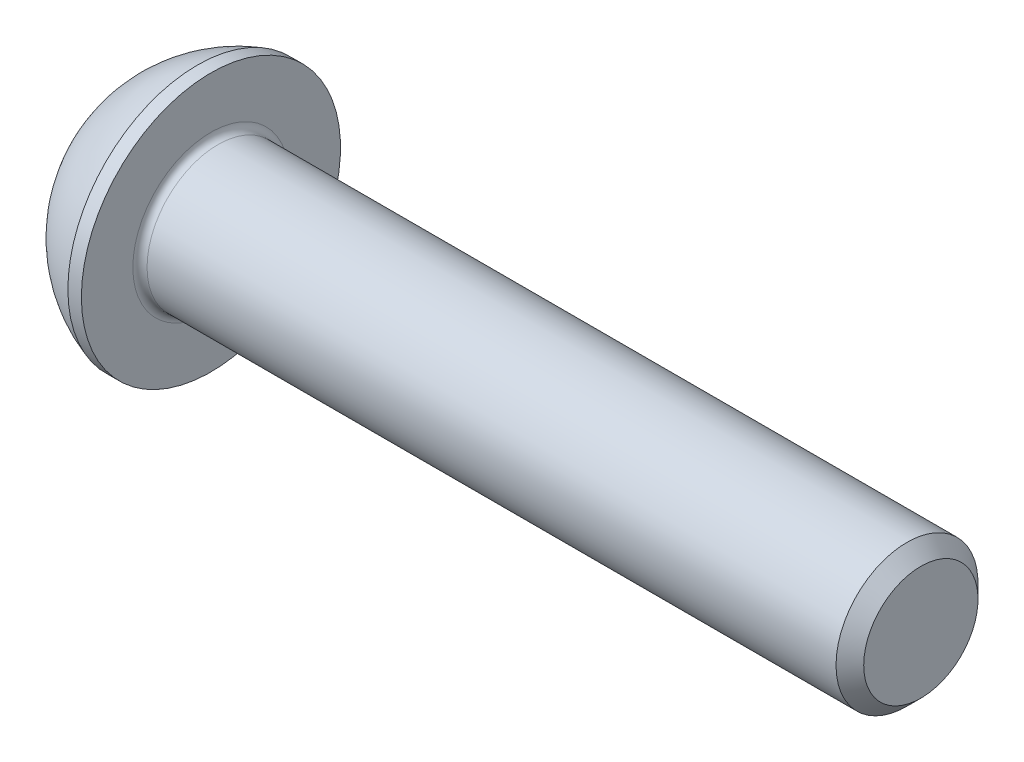
SolidWorks part; units mm, degrees
ref_plane "Plane1" through (0, 0, 0) normal (0, 0, 1) x (1, 0, 0)
ref_plane "Plane2" through (0, 0, 0) normal (0, 1, 0) x (1, 0, 0)
ref_plane "Plane3" through (0, 0, 0) normal (1, 0, 0) x (0, 0, -1)
sketch "BodySke" plane through (0, 0, 0) normal (0, 0, 1) x (1, 0, 0)
  line L0 (22.6, 0) -> (22.6, 1.61)
  line L1 (22.21, 2) -> (2.6, 2)
  line L2 (2.6, 2) -> (2.6, 3.65)
  line L3 (2.6, 3.65) -> (2.22, 3.65)
  line L4 (0, 0) -> (101.6, 0) construction
  line L5 (2.6, -3.65) -> (2.22, -3.65) construction
  line L6 (55.6768, -2) -> (2.6, -2) construction
  line L7 (22.6, 0) -> (0, 0)
  line L8 (0, 1.825) -> (0, -1.825) construction
  line L9 (0, 0) -> (0, 1.825)
  line L10 (22.6, 1.61) -> (22.21, 2)
  line L11 (22.6, -1.61) -> (22.21, -2) construction
  line L12 (3.3, 9.525) -> (3.3, -2) construction
  line L13 (2.6, 9.525) -> (2.6, -2) construction
  arc A1 (0, 1.825) -> (2.22, 3.65) centre (3.3604, 0) cw
  dimension "D1" = 3.65
  dimension "Diameter" = 4
  dimension "Length" = 20
  dimension "Head_dia" = 7.3
  dimension "Head_ht" = 2.6
  dimension "Head_side_ht" = 0.38
  dimension "Minor_dia" = 3.22
  dimension "Body_ch_ang" = 45
  dimension "Advance" = 0.7
  dimension "Thread_nom" = 20
revolve "BaseBody" add sketch "BodySke" angle 360 about L4
cosmetic thread "ThreadCosmetic" parameters "Thread_length"=18.6, "Thread_minor"=3.22
fillet "Fillet1" radius 0.2 1 edges at (2.6, 0, 2)
sketch "Sketch2" plane through (0, 0, 0) normal (0, 0, 1) x (1, 0, 0)
  line L0 (0, 1.25) -> (1.3, 1.25)
  line L1 (1.3, 1.25) -> (2.0217, 0)
  line L3 (2.0217, 0) -> (0, 0)
  line L4 (0, 0) -> (0, 1.25)
  line L5 (0, -1.25) -> (1.3, -1.25) construction
  line L6 (0, 0) -> (47.625, 0) construction
  dimension "D2" = 60
  dimension "PreBroach_depth" = 1.3
  dimension "PreBroach_dia" = 2.5
revolve "PreBroach" cut sketch "Sketch2" angle 360 about L6
sketch "Sketch3" plane through (0, 0, 0) normal (1, 0, 0) x (0, 0, -1)
  line L0 (-1.25, -0.7217) -> (-1.25, 0.7217)
  line L1 (-1.25, 0.7217) -> (0, 1.4434)
  line L2 (0, 1.4434) -> (1.25, 0.7217)
  line L3 (1.25, 0.7217) -> (1.25, -0.7217)
  line L4 (1.25, -0.7217) -> (0, -1.4434)
  line L5 (0, -1.4434) -> (-1.25, -0.7217)
  dimension "D1" = 1.25
  dimension "D2" = 1.25
  dimension "D3" = 2.5
  dimension "Hex_size" = 2.5
extrude "Hex" cut sketch "Sketch3" along normal blind 1.3
sketch "ThdSchSke" plane through (0, 0, 0) normal (0, 0, 1) x (1, 0, 0)
  line L0 (4, -1.61) -> (3.7269, -2)
  line L1 (4, -1.61) -> (4.2731, -2)
  line L2 (4.2731, -2) -> (4.2731, -2.5)
  line L3 (-3.175, 0) -> (5.1513, 0) construction
  line L5 (4.2731, -2.5) -> (3.7269, -2.5)
  line L6 (3.7269, -2.5) -> (3.7269, -2)
  dimension "Thread_minor" = 3.22
  dimension "Diameter" = 4
  dimension "Start" = 4
  dimension "SideAngle" = 55
  dimension "VeeAngle" = 70
  dimension "Overcut" = 5
revolve "ThreadSchematic" [suppressed] cut sketch "ThdSchSke" angle 360 about L3
pattern_linear "ThdSchPat" [suppressed]
equation "\"D1@BodySke\" = \"Head_dia@BodySke\" * .5"
equation "\"Thread_minor@ThreadCosmetic\" = \"Minor_dia@BodySke\""
equation "\"D1@Sketch3\" = \"Hex_size@Sketch3\" / 2"
equation "\"D2@Sketch3\" = \"D1@Sketch3\""
equation "\"D3@Sketch3\" = \"Hex_size@Sketch3\""
equation "\"Thread_length@ThreadCosmetic\" = ((sgn( (\"Length@BodySke\" - \"Advance@BodySke\" * 2.0) - \"Thread_nom@BodySke\" )-1)*( (\"Length@BodySke\" - \"Advance@BodySke\" * 2.0) - \"Thread_nom@BodySke\" ))/-2+ \"Thread_nom@BodySke\""
equation "\"Thread_minor@ThdSchSke\" = \"Minor_dia@BodySke\""
equation "\"Diameter@ThdSchSke\" = \"Diameter@BodySke\""
equation "\"Overcut@ThdSchSke\" = \"Diameter@BodySke\" * 1.25"
equation "\"Start@ThdSchSke\" = \"Head_ht@BodySke\" + \"Length@BodySke\" - \"Thread_length@ThreadCosmetic\"  '---Non-countersunk---"
equation "\"Num_threads@ThdSchPat\" = int( \"Thread_length@ThreadCosmetic\" / \"Advance@BodySke\" + 0.999 )  + 1"
equation "\"Advance@ThdSchPat\" = \"Thread_length@ThreadCosmetic\" /  (\"Num_threads@ThdSchPat\" - 1) 'relax it"
equation "\"Num_threads@ThdSchPat\" = \"Num_threads@ThdSchPat\" - sgn( \"Num_threads@ThdSchPat\" - 1) '---chamfered tips only---"
